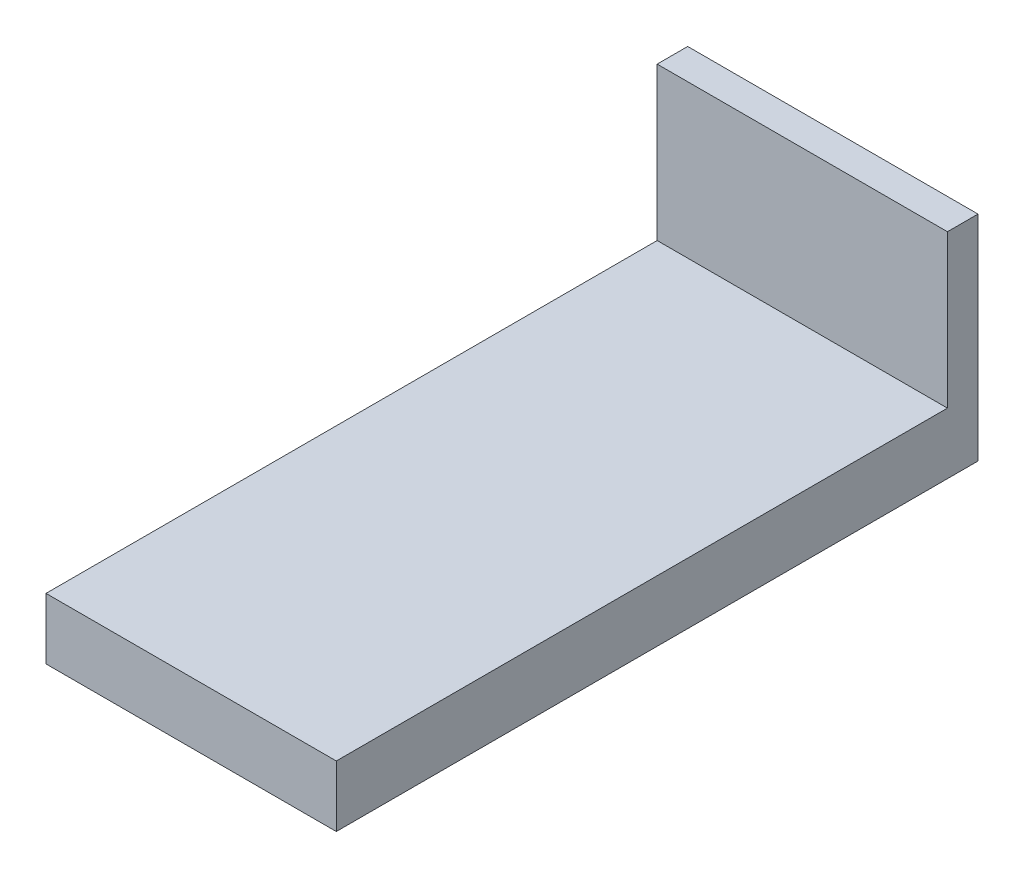
SolidWorks part; units mm, degrees
ref_plane "Front Plane" through (0, 0, 0) normal (0, 0, 1) x (1, 0, 0)
ref_plane "Top Plane" through (0, 0, 0) normal (0, 1, 0) x (1, 0, 0)
ref_plane "Right Plane" through (0, 0, 0) normal (1, 0, 0) x (0, 0, -1)
sketch "Sketch1" plane through (0, 0, 0) normal (0, 1, 0) x (1, 0, 0)
  line L1 (-475, 1000) -> (475, 1000)
  line L2 (-475, 1000) -> (-475, -1000)
  line L3 (-475, -1000) -> (475, -1000)
  line L4 (475, 1000) -> (475, -1000)
  line L5 (-475, 1000) -> (475, -1000) construction
  line L6 (-475, -1000) -> (475, 1000) construction
  point P0 (0, 0)
  dimension "D1" = 2000
  dimension "D2" = 950
extrude "Boss-Extrude1" add sketch "Sketch1" along normal blind 200
sketch "Sketch2" plane through (0, 0, 0) normal (0, -1, 0) x (1, 0, 0)
  line L0 (475, 1000) -> (475, -1000) construction
  line L1 (-475, -1000) -> (475, -1000)
  line L2 (-475, -1000) -> (-475, -1100)
  line L3 (-475, -1100) -> (475, -1100)
  line L4 (475, -1000) -> (475, -1100)
  dimension "D1" = 100
extrude "Boss-Extrude2" add sketch "Sketch2" against normal blind 700
